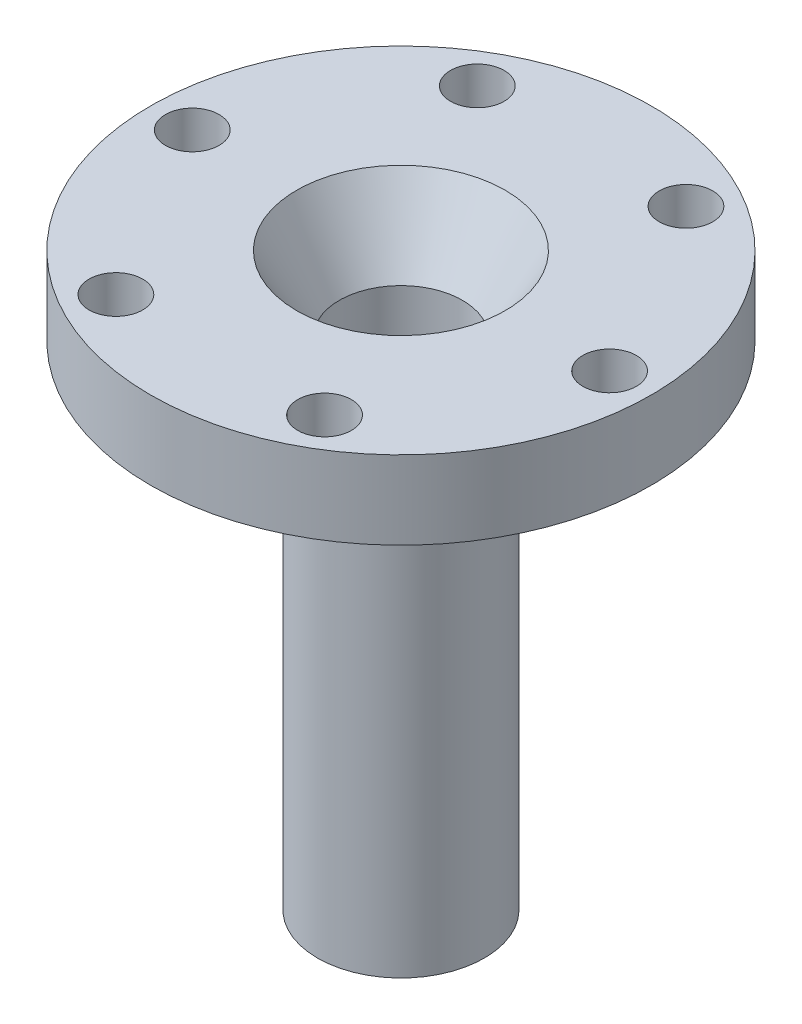
SolidWorks part; units mm, degrees
material "AISI Type 316L stainless steel"
ref_plane "Front Plane" through (0, 0, 0) normal (0, 0, 1) x (1, 0, 0)
ref_plane "Top Plane" through (0, 0, 0) normal (0, 1, 0) x (1, 0, 0)
ref_plane "Right Plane" through (0, 0, 0) normal (1, 0, 0) x (0, 0, -1)
sketch "Sketch1" plane through (0, 0, 0) normal (0, 0, 1) x (1, 0, 0)
  line L0 (0, 0) -> (0, -29.8554) construction
  line L1 (7.5, -69.525) -> (7.5, -9.0067)
  line L2 (7.5, -9.0067) -> (12.7, 0)
  line L3 (12.7, 0) -> (30.48, 0)
  line L4 (30.48, 0) -> (30.48, -9.525)
  line L5 (30.48, -9.525) -> (10.16, -9.525)
  line L6 (10.16, -9.525) -> (10.16, -69.525)
  line L7 (10.16, -69.525) -> (7.5, -69.525)
  dimension "D1" = 20.32
  dimension "D2" = 15
  dimension "D3" = 60
  dimension "D4" = 30
  dimension "D5" = 25.4
  dimension "D6" = 60.96
  dimension "D7" = 9.525
revolve "Revolve1" add sketch "Sketch1" angle 360 about L0
hole_wizard "1/4 Clearance Hole1" positions "Sketch3" profile "Sketch4" hole size "1/4" standard "ANSI Inch" end condition through all
sketch "Sketch3" plane through (0, 0, 0) normal (0, 1, 0) x (1, 0, 0)
  line L0 (25.4, 0) -> (0, 0) construction
  point P0 (25.4, 0)
  dimension "D1" = 25.4
sketch "Sketch4" plane through (25.4, 0, 0) normal (1, 0, 0) x (0, 0, 1)
  line L0 (0, 0) -> (0, 69.525)
  line L1 (0, 69.525) -> (3.2639, 69.525)
  line L2 (3.2639, 69.525) -> (3.2639, 0)
  line L5 (3.2639, 0) -> (0, 0)
  line L11 (0, -6.35) -> (0, 107.95) construction
  dimension "Thru Hole Dia." = 6.5278
  dimension "Thru Hole Depth" = 69.525
pattern_circular "CirPattern1" count 6 over 360 about axis through (0, 0, 0) along (0, 1, 0) of "1/4 Clearance Hole1"
sketch "Sketch5" plane through (0, 0, 0) normal (0, 1, 0) x (1, 0, 0)
  circle A0 centre (0, 0) radius 25.4
  dimension "D1" = 50.8
chamfer "Chamfer1" distance 2.032 angle 22 1 edges at (0, -69.525, 7.5)
fillet "Fillet1" radius 0.7937 1 edges at (0, -68.704, 7.5)
chamfer "Chamfer2" distance 3.175 angle 45 1 edges at (0, -9.525, 10.16)
